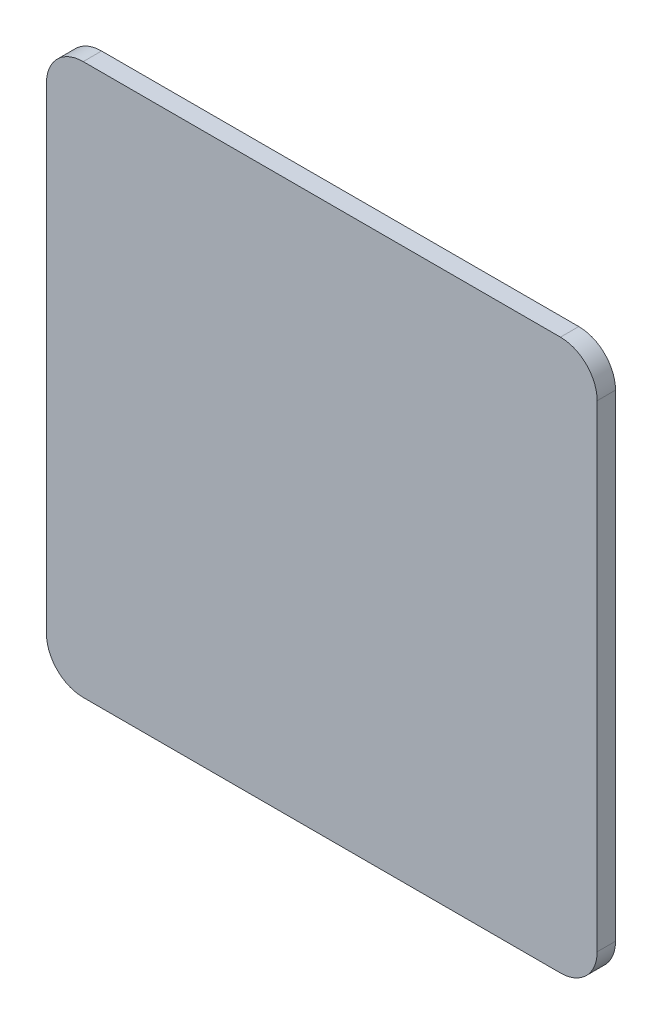
SolidWorks part; units mm, degrees
ref_plane "Front Plane" through (0, 0, 0) normal (0, 0, 1) x (1, 0, 0)
ref_plane "Top Plane" through (0, 0, 0) normal (0, 1, 0) x (1, 0, 0)
ref_plane "Right Plane" through (0, 0, 0) normal (1, 0, 0) x (0, 0, -1)
sketch "Sketch1" plane through (0, 0, 0) normal (0, 0, 1) x (1, 0, 0)
  line L1 (0, 0) -> (30, 0)
  line L2 (0, 0) -> (0, 30)
  line L3 (0, 30) -> (30, 30)
  line L4 (30, 0) -> (30, 30)
  dimension "D1" = 30
  dimension "D2" = 30
extrude "Boss-Extrude1" add sketch "Sketch1" along normal blind 1
fillet "Fillet1" radius 2 4 edges at (0, 0, 0.5) (30, 0, 0.5) (0, 30, 0.5) (30, 30, 0.5)
